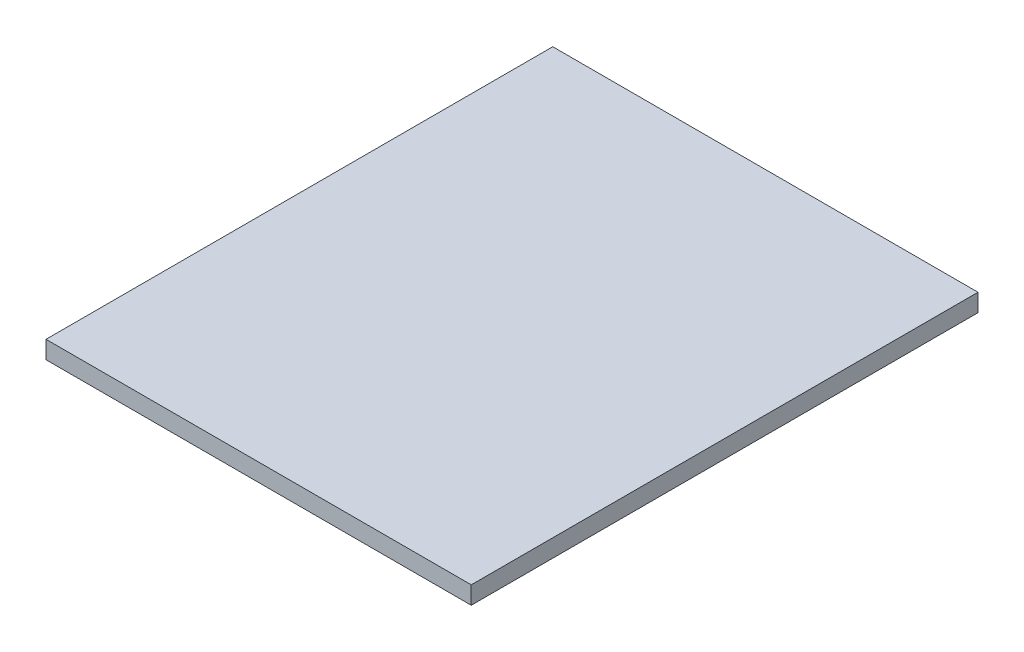
SolidWorks part; units mm, degrees
ref_plane "Front Plane" through (0, 0, 0) normal (0, 0, 1) x (1, 0, 0)
ref_plane "Top Plane" through (0, 0, 0) normal (0, 1, 0) x (1, 0, 0)
ref_plane "Right Plane" through (0, 0, 0) normal (1, 0, 0) x (0, 0, -1)
sketch "Sketch1" plane through (0, 0, 0) normal (0, 1, 0) x (1, 0, 0)
  line L1 (-38.1, -45.4025) -> (38.1, -45.4025)
  line L2 (-38.1, -45.4025) -> (-38.1, 45.4025)
  line L3 (-38.1, 45.4025) -> (38.1, 45.4025)
  line L4 (38.1, -45.4025) -> (38.1, 45.4025)
  line L5 (-38.1, -45.4025) -> (38.1, 45.4025) construction
  line L6 (-38.1, 45.4025) -> (38.1, -45.4025) construction
  point P0 (0, 0)
  dimension "D1" = 90.805
  dimension "D2" = 76.2
extrude "Boss-Extrude1" add sketch "Sketch1" along normal blind 3.175
